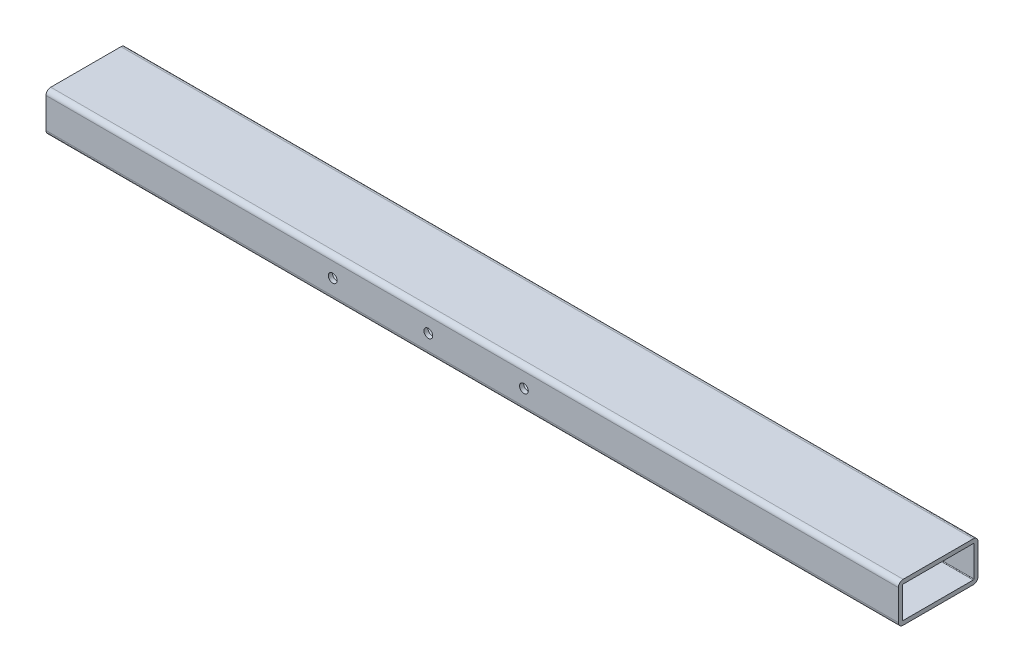
SolidWorks part; units mm, degrees
ref_plane "Plano frontal" through (0, 0, 0) normal (0, 0, 1) x (1, 0, 0)
ref_plane "Plano superior" through (0, 0, 0) normal (0, 1, 0) x (1, 0, 0)
ref_plane "Plano direito" through (0, 0, 0) normal (1, 0, 0) x (0, 0, -1)
sketch "Esboço1" plane through (0, 0, 0) normal (0, 0, 1) x (1, 0, 0)
  line L0 (0, 0) -> (535, 0)
  dimension "D1" = 535
other "Tubo retangular 50 X 30 X 2.6(1)"
ref_plane "Plano1" through (0, 0, 0) normal (1, 0, 0) x (0, 1, 0)
sketch "Sketch1" plane through (0, 0, 0) normal (1, 0, 0) x (0, 1, 0)
  line L0 (-9.5, -22.4) -> (9.5, -22.4)
  line L1 (-9.9, -22) -> (-9.9, 22)
  line L2 (9.5, 22.4) -> (-9.5, 22.4)
  line L3 (9.9, 22) -> (9.9, -22)
  line L4 (-9.5, -25) -> (9.5, -25)
  line L5 (-12.5, -22) -> (-12.5, 22)
  line L6 (9.5, 25) -> (-9.5, 25)
  line L7 (12.5, 22) -> (12.5, -22)
  arc A0 (12.5, 22) -> (9.5, 25) centre (9.5, 22) ccw
  arc A1 (9.5, -25) -> (12.5, -22) centre (9.5, -22) ccw
  arc A2 (-12.5, -22) -> (-9.5, -25) centre (-9.5, -22) ccw
  arc A3 (-9.5, 25) -> (-12.5, 22) centre (-9.5, 22) ccw
  arc A4 (-9.5, 22.4) -> (-9.9, 22) centre (-9.5, 22) ccw
  arc A5 (9.9, 22) -> (9.5, 22.4) centre (9.5, 22) ccw
  arc A6 (9.5, -22.4) -> (9.9, -22) centre (9.5, -22) ccw
  arc A7 (-9.9, -22) -> (-9.5, -22.4) centre (-9.5, -22) ccw
  point P0 (0, 25)
  point P1 (12.5, 0)
  point P2 (0, -25)
  point P3 (-12.5, 0)
  point P4 (-12.5, 25)
  point P5 (12.5, 25)
  point P6 (12.5, -25)
  point P7 (-12.5, -25)
  point P8 (0, 0)
  point P33 (0, 0)
  dimension "D1" = 3
  dimension "Thickness" = 2.6
  dimension "V_leg" = 50
  dimension "H_leg" = 25
sketch "Esboço2" plane through (0, 0, -25) normal (0, 0, -1) x (-1, 0, 0)
  circle A0 centre (-179.9738, 0.2) radius 2.75
  circle A1 centre (-239.9738, 0.2) radius 2.75
  circle A2 centre (-299.9738, 0.2) radius 2.75
extrude "Corte-extrusão1" cut sketch "Esboço2" against normal through all
